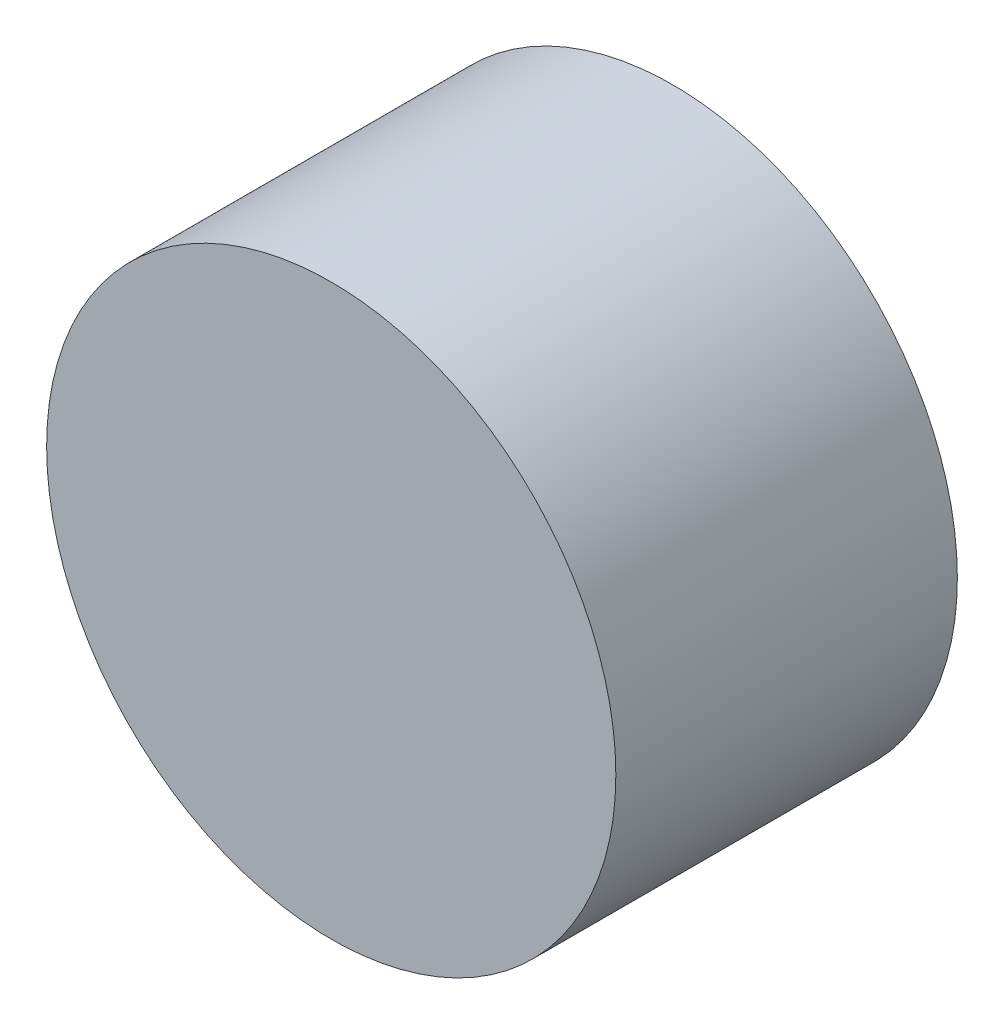
SolidWorks part; units mm, degrees
ref_plane "Plan de face" through (0, 0, 0) normal (0, 0, 1) x (1, 0, 0)
ref_plane "Plan de dessus" through (0, 0, 0) normal (0, 1, 0) x (1, 0, 0)
ref_plane "Plan de droite" through (0, 0, 0) normal (1, 0, 0) x (0, 0, -1)
sketch "Esquisse1" plane through (0, 0, 0) normal (0, 0, 1) x (1, 0, 0)
  circle A0 centre (0, 0) radius 10
  dimension "D1" = 20
extrude "Boss.-Extru.1" add sketch "Esquisse1" along normal blind 12
